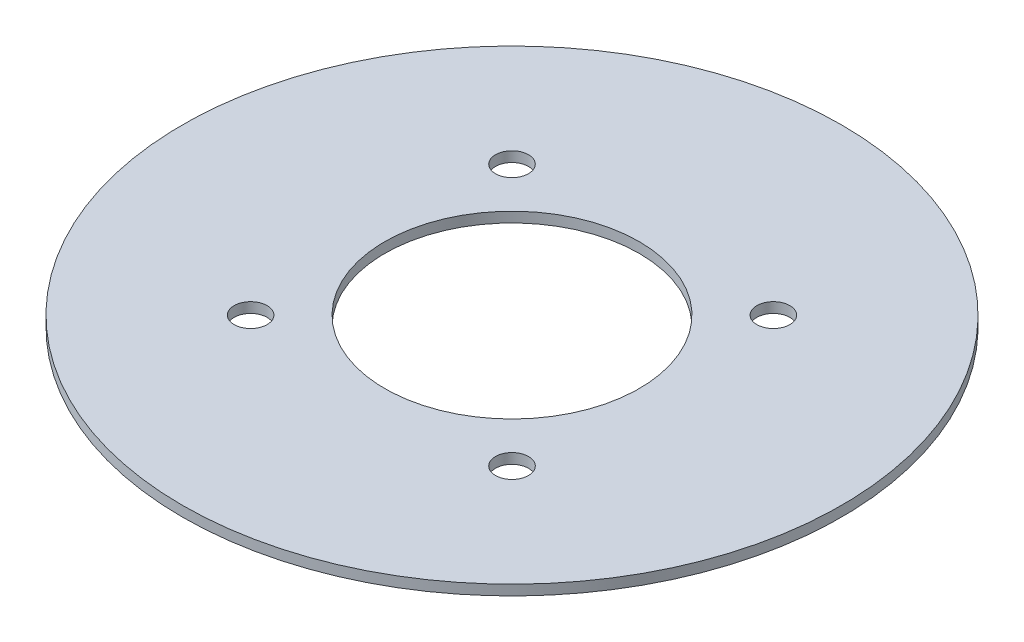
SolidWorks part; units mm, degrees
ref_plane "前视基准面" through (0, 0, 0) normal (0, 0, 1) x (1, 0, 0)
ref_plane "上视基准面" through (0, 0, 0) normal (0, 1, 0) x (1, 0, 0)
ref_plane "右视基准面" through (0, 0, 0) normal (1, 0, 0) x (0, 0, -1)
other "Configuration Table"
sketch "草图1" plane through (0, 604.0036, 0) normal (0, -1, 0) x (1, 0, 0)
  circle A0 centre (0, 0) radius 29
extrude "凸台-拉伸1" add sketch "草图1" along normal blind 0.9
sketch "草图2" plane through (0, 603.1036, 0) normal (0, -1, 0) x (1, 0, 0)
  circle A0 centre (11.5, -11.5) radius 1.45 construction
  circle A1 centre (-11.5, -11.5) radius 1.45 construction
  circle A2 centre (11.5, 11.5) radius 1.45 construction
  circle A3 centre (-11.5, 11.5) radius 1.45 construction
  circle A4 centre (0, 0) radius 11.2 construction
  circle A5 centre (11.5, -11.5) radius 1.45
  circle A6 centre (-11.5, -11.5) radius 1.45
  circle A7 centre (11.5, 11.5) radius 1.45
  circle A8 centre (-11.5, 11.5) radius 1.45
  circle A9 centre (0, 0) radius 11.2
extrude "切除-拉伸1" cut sketch "草图2" against normal blind 0.9
